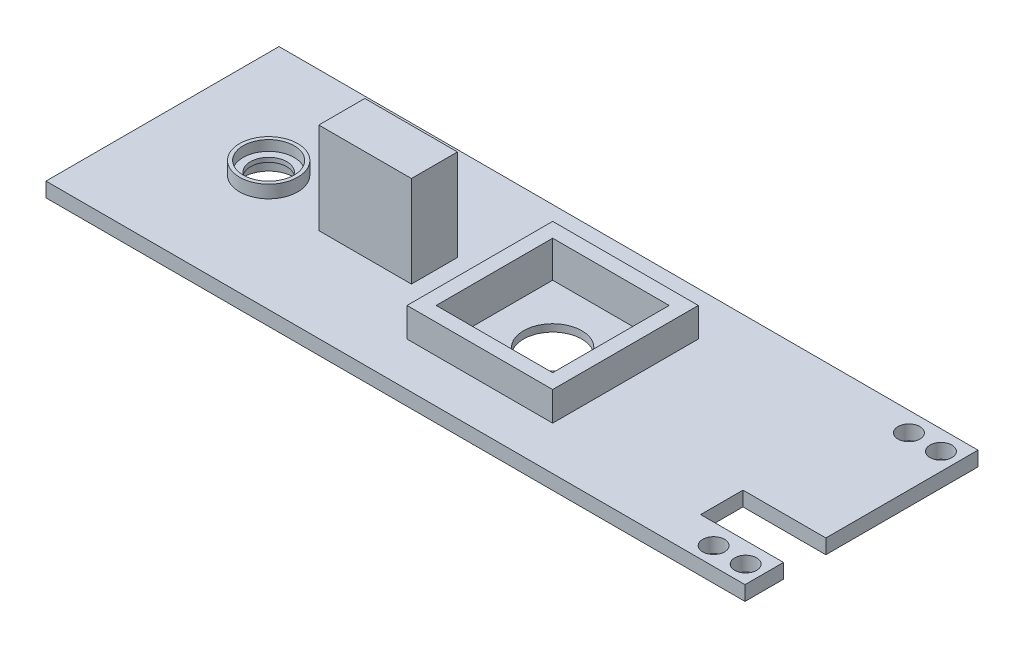
SolidWorks part; units mm, degrees
ref_plane "Front Plane" through (0, 0, 0) normal (0, 0, 1) x (1, 0, 0)
ref_plane "Top Plane" through (0, 0, 0) normal (0, 1, 0) x (1, 0, 0)
ref_plane "Right Plane" through (0, 0, 0) normal (1, 0, 0) x (0, 0, -1)
sketch "Sketch1" plane through (0, 0, 0) normal (0, 1, 0) x (1, 0, 0)
  line L1 (-304.8, -50.8) -> (0, -50.8)
  line L2 (-304.8, -50.8) -> (-304.8, 50.8)
  line L3 (-304.8, 50.8) -> (0, 50.8)
  line L4 (0, -50.8) -> (0, 50.8)
  point P0 (0, 0)
  dimension "D1" = 304.8
  dimension "D2" = 101.6
extrude "Boss-Extrude1" add sketch "Sketch1" along normal blind 6.35
sketch "Sketch2" plane through (0, 6.35, 0) normal (0, 1, 0) x (1, 0, 0)
  circle A0 centre (-258.5106, 0) radius 12.7
extrude "Boss-Extrude3" add sketch "Sketch2" along normal blind 5.5562
sketch "Sketch9" plane through (0, 11.9062, 0) normal (0, 1, 0) x (1, 0, 0)
  circle A0 centre (-258.5106, 0) radius 11.1125
extrude "Cut-Extrude4" cut sketch "Sketch9" against normal blind 4.445
sketch "Sketch10" plane through (0, 0, 0) normal (0, -1, 0) x (-1, 0, 0)
  circle A0 centre (258.5106, 0) radius 11.1125
extrude "Cut-Extrude5" cut sketch "Sketch10" against normal blind 5.5562
sketch "Sketch11" plane through (0, 7.4613, 0) normal (0, 1, 0) x (1, 0, 0)
  circle A0 centre (-258.5106, 0) radius 7.9375
extrude "Cut-Extrude6" cut sketch "Sketch11" against normal through all
sketch "Sketch12" plane through (0, 6.35, 0) normal (0, 1, 0) x (1, 0, 0)
  circle A0 centre (-134.6662, 0) radius 12.7
  dimension "D1" = 25.4
extrude "Cut-Extrude7" cut sketch "Sketch12" against normal through all
sketch "Sketch22" plane through (0, 6.35, 0) normal (0, 1, 0) x (1, 0, 0)
  line L1 (-102.9162, -31.75) -> (-166.4162, -31.75)
  line L2 (-102.9162, -31.75) -> (-102.9162, 31.75)
  line L3 (-102.9162, 31.75) -> (-166.4162, 31.75)
  line L4 (-166.4162, -31.75) -> (-166.4162, 31.75)
  line L5 (-102.9162, -31.75) -> (-166.4162, 31.75) construction
  line L6 (-102.9162, 31.75) -> (-166.4162, -31.75) construction
  circle A0 centre (-134.6662, 0) radius 12.7 construction
  point P0 (-134.6662, 0)
extrude "Boss-Extrude7" add sketch "Sketch22" along normal blind 12.7
sketch "Sketch25" plane through (0, 19.05, 0) normal (0, 1, 0) x (1, 0, 0)
  line L1 (-109.2662, -25.4) -> (-160.0662, -25.4)
  line L2 (-109.2662, -25.4) -> (-109.2662, 25.4)
  line L3 (-109.2662, 25.4) -> (-160.0662, 25.4)
  line L4 (-160.0662, -25.4) -> (-160.0662, 25.4)
  line L5 (-109.2662, -25.4) -> (-160.0662, 25.4) construction
  line L6 (-109.2662, 25.4) -> (-160.0662, -25.4) construction
  circle A0 centre (-134.6662, 0) radius 12.7 construction
  point P0 (-134.6662, 0)
  dimension "D1" = 50.8
  dimension "D2" = 50.8
extrude "Cut-Extrude11" cut sketch "Sketch25" against normal blind 15.875
sketch "Sketch18" plane through (0, 6.35, 0) normal (0, 1, 0) x (1, 0, 0)
  line L2 (-226.612, -10.033) -> (-186.226, -10.033)
  line L3 (-226.612, -10.033) -> (-226.612, 10.033)
  line L4 (-226.612, 10.033) -> (-186.226, 10.033)
  line L5 (-186.226, -10.033) -> (-186.226, 10.033)
extrude "Boss-Extrude5" add sketch "Sketch18" along normal blind 39.878 contours L3 L2 L5 L4
sketch "Sketch32" plane through (0, 6.35, 0) normal (0, 1, 0) x (1, 0, 0)
  line L0 (0, 50.8) -> (-304.8, 50.8) construction
  line L1 (-304.8, -50.8) -> (0, -50.8) construction
  line L2 (0, -50.8) -> (0, 50.8) construction
  circle A0 centre (-7.62, -42.8938) radius 4.7625
  circle A1 centre (-21.59, -42.8938) radius 4.7625
  circle A2 centre (-7.62, 42.2729) radius 4.7625
  circle A3 centre (-21.59, 42.2729) radius 4.7625
  dimension "D1" = 9.525
  dimension "D2" = 9.525
  dimension "D3" = 9.525
  dimension "D4" = 9.525
  dimension "D5" = 8.5271
  dimension "D6" = 7.62
  dimension "D7" = 8.5271
  dimension "D8" = 21.59
  dimension "D9" = 7.9062
  dimension "D10" = 7.62
  dimension "D11" = 7.9062
  dimension "D12" = 21.59
extrude "Cut-Extrude12" cut sketch "Sketch32" against normal blind 6.35
sketch "Sketch34" plane through (0, 6.35, 0) normal (0, 1, 0) x (1, 0, 0)
  line L0 (-304.8, -50.8) -> (0, -50.8) construction
  line L1 (0, -15.5426) -> (-36.1331, -15.5426)
  line L2 (0, -15.5426) -> (0, -34.0128)
  line L3 (0, -34.0128) -> (-36.1331, -34.0128)
  line L4 (-36.1331, -15.5426) -> (-36.1331, -34.0128)
  dimension "D2" = 16.7872
  dimension "D3" = 36.1331
  dimension "D4" = 18.4703
extrude "Cut-Extrude13" cut sketch "Sketch34" against normal through all
